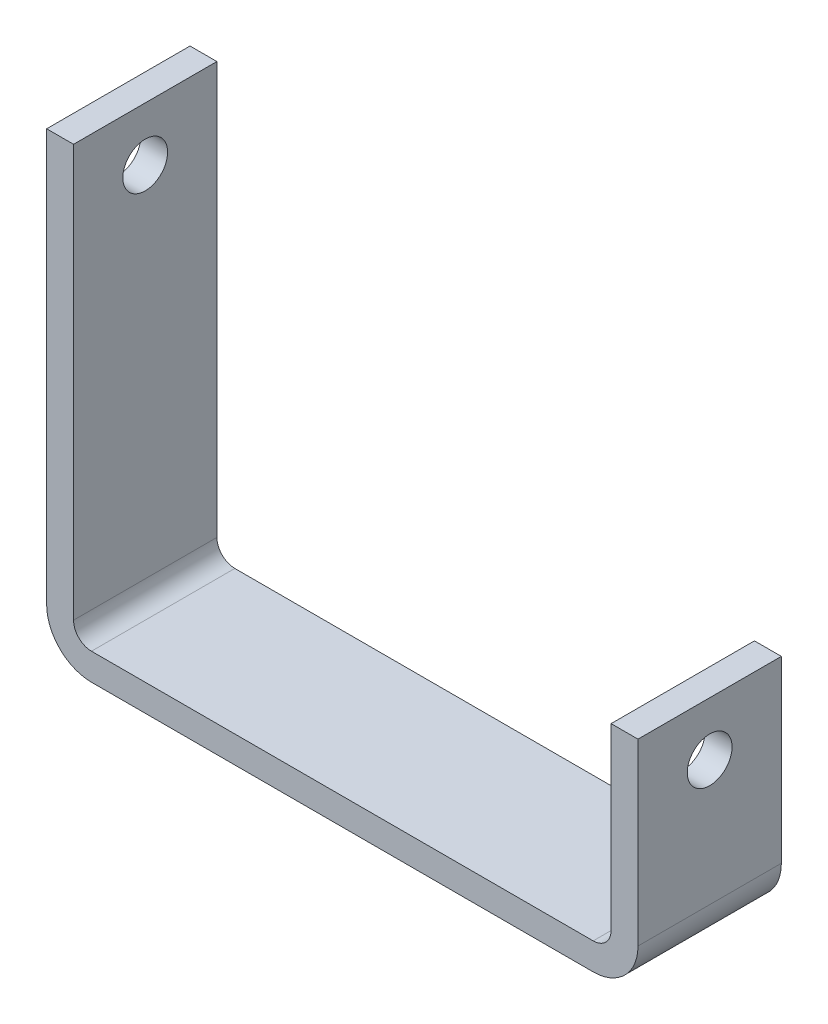
SolidWorks part; units mm, degrees
ref_plane "front" through (0, 0, 0) normal (0, 0, 1) x (1, 0, 0)
ref_plane "top" through (0, 0, 0) normal (0, 1, 0) x (1, 0, 0)
ref_plane "right" through (0, 0, 0) normal (1, 0, 0) x (0, 0, -1)
sketch "Sketch1" plane through (0, 0, 0) normal (0, 0, 1) x (1, 0, 0)
  line L1 (0, 0) -> (150, 0)
  line L2 (0, 0) -> (0, 120)
  line L4 (150, 0) -> (150, 55)
  dimension "D1" = 120
  dimension "D2" = 150
  dimension "D3" = 55
extrude "Base-Extrude-Thin" add sketch "Sketch1" along normal mid plane 40 thin
sketch "Sketch2" plane through (0, 88.9, 0) normal (-1, 0, 0) x (0, -1, 0)
  line L2 (83.9, 20) -> (-31.1, 20) construction
  line L3 (-31.1, 20) -> (-31.1, -20) construction
  circle A0 centre (-16.1, 0) radius 6.25
  dimension "D1" = 20
  dimension "D2" = 15
  dimension "D3" = 12.5
extrude "Cut-Extrude1" cut sketch "Sketch2" along normal up to next
sketch "Sketch3" plane through (157.5, 0, 0) normal (1, 0, 0) x (0, 0, -1)
  line L0 (-20, 55) -> (20, 55) construction
  line L1 (-20, 55) -> (-20, 5) construction
  circle A0 centre (0, 40) radius 6.25
  dimension "D1" = 12.5
  dimension "D2" = 15
  dimension "D3" = 20
extrude "Cut-Extrude2" cut sketch "Sketch3" against normal up to next
